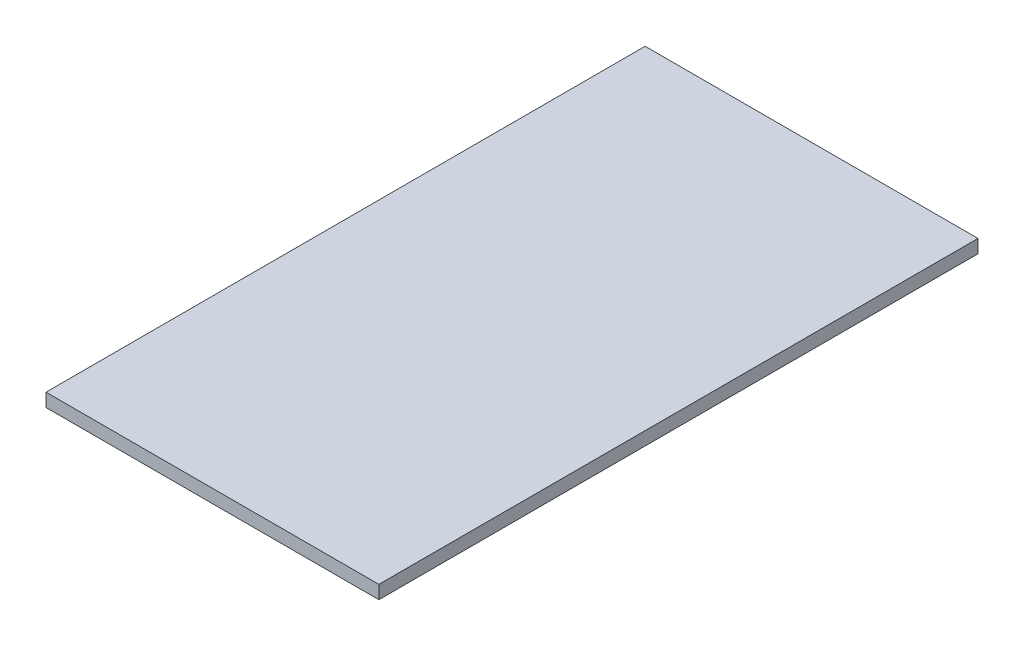
SolidWorks part; units mm, degrees
ref_plane "Front Plane" through (0, 0, 0) normal (0, 0, 1) x (1, 0, 0)
ref_plane "Top Plane" through (0, 0, 0) normal (0, 1, 0) x (1, 0, 0)
ref_plane "Right Plane" through (0, 0, 0) normal (1, 0, 0) x (0, 0, -1)
sketch "Sketch1" plane through (0, 0, 0) normal (0, 1, 0) x (1, 0, 0)
  line L1 (-25, -45) -> (25, -45)
  line L2 (-25, -45) -> (-25, 45)
  line L3 (-25, 45) -> (25, 45)
  line L4 (25, -45) -> (25, 45)
  line L5 (-25, -45) -> (25, 45) construction
  line L6 (-25, 45) -> (25, -45) construction
  point P0 (0, 0)
  dimension "D1" = 50
  dimension "D2" = 90
extrude "Boss-Extrude1" add sketch "Sketch1" along normal blind 2
